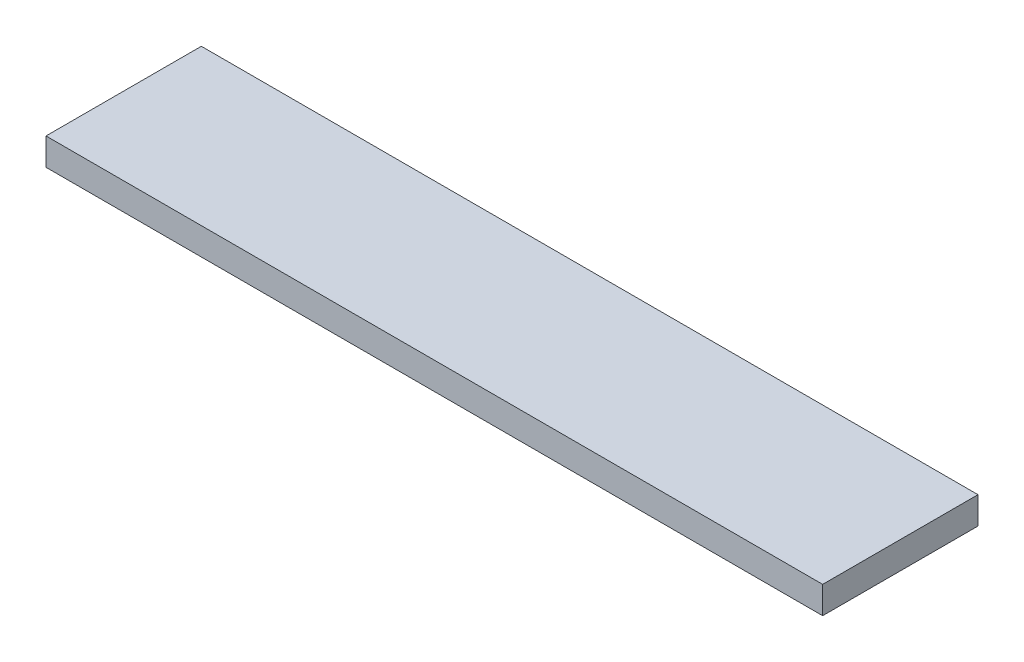
SolidWorks part; units mm, degrees
ref_plane "Front Plane" through (0, 0, 0) normal (0, 0, 1) x (1, 0, 0)
ref_plane "Top Plane" through (0, 0, 0) normal (0, 1, 0) x (1, 0, 0)
ref_plane "Right Plane" through (0, 0, 0) normal (1, 0, 0) x (0, 0, -1)
sketch "Sketch1" plane through (0, 0, 0) normal (1, 0, 0) x (0, 0, -1)
  line L1 (-20, 3.5) -> (20, 3.5)
  line L2 (-20, 3.5) -> (-20, -3.5)
  line L3 (-20, -3.5) -> (20, -3.5)
  line L4 (20, 3.5) -> (20, -3.5)
  line L5 (-20, 3.5) -> (20, -3.5) construction
  line L6 (-20, -3.5) -> (20, 3.5) construction
  point P0 (0, 0)
  dimension "D1" = 40
  dimension "D2" = 7
extrude "Boss-Extrude1" add sketch "Sketch1" along normal blind 200
